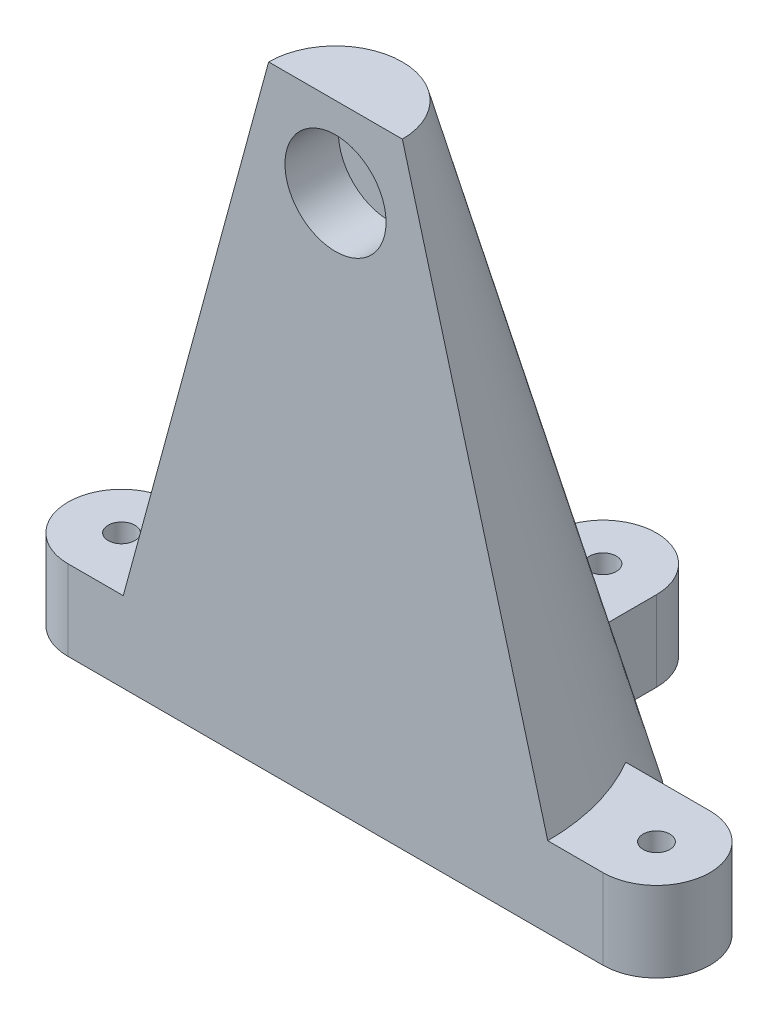
SolidWorks part; units mm, degrees
ref_plane "Front Plane" through (0, 0, 0) normal (0, 0, 1) x (1, 0, 0)
ref_plane "Top Plane" through (0, 0, 0) normal (0, 1, 0) x (1, 0, 0)
ref_plane "Right Plane" through (0, 0, 0) normal (1, 0, 0) x (0, 0, -1)
sketch "Sketch1" plane through (0, 0, 0) normal (0, 1, 0) x (1, 0, 0)
  line L0 (-22.225, 0) -> (22.225, 0)
  circle A0 centre (0, 0) radius 22.225 construction
  arc A1 (22.225, 0) -> (-22.225, 0) centre (0, 0) ccw
  point P6 (0, 0)
  point P7 (-22.2163, 0.6222)
  dimension "D1" = 44.45
ref_plane "Plane1" through (0, 58.42, 0) normal (0, 1, 0) x (1, 0, 0)
sketch "Sketch2" plane through (0, 58.42, 0) normal (0, 1, 0) x (1, 0, 0)
  line L0 (-22.225, 0) -> (22.225, 0) construction
  line L1 (-6.35, 0) -> (6.35, 0)
  circle A0 centre (0, 0) radius 6.35 construction
  arc A1 (6.35, 0) -> (-6.35, 0) centre (0, 0) ccw
  point P4 (-6.35, 0.1606)
  point P7 (0, 0)
  dimension "D1" = 12.7
loft "Loft1" add profiles "Sketch1", "Sketch2"
sketch "Sketch3" plane through (0, 0, 0) normal (0, 1, 0) x (1, 0, 0)
  line L0 (0, 0) -> (0, 25.4) construction
  line L1 (5.08, 25.4) -> (5.08, 10.16)
  line L2 (5.08, 10.16) -> (25.4, 10.16)
  line L3 (25.4, 0) -> (-25.4, 0)
  line L4 (-6.35, 0) -> (6.35, 0) construction
  line L5 (-5.08, 25.4) -> (-5.08, 10.16)
  line L6 (-5.08, 10.16) -> (-25.4, 10.16)
  arc A0 (-5.08, 25.4) -> (5.08, 25.4) centre (0, 25.4) cw
  arc A1 (25.4, 10.16) -> (25.4, 0) centre (25.4, 5.08) cw
  circle A2 centre (25.4, 5.08) radius 1.27
  circle A3 centre (-25.4, 5.08) radius 1.27
  arc A4 (-25.4, 10.16) -> (-25.4, 0) centre (-25.4, 5.08) ccw
  circle A5 centre (0, 25.4) radius 1.27
  point P19 (0, 0)
  point P20 (0, 30.8133)
  point P21 (0, 25.6327)
  dimension "D4" = 2.54
  dimension "D1" = 10.16
  dimension "D2" = 25.4
  dimension "D3" = 25.4
extrude "Boss-Extrude1" add sketch "Sketch3" along normal blind 7.62
sketch "Sketch4" plane through (0, 0, 0) normal (0, 0, 1) x (1, 0, 0)
  line L0 (0, 50.8) -> (0, 0) construction
  line L1 (-25.4, 0) -> (25.4, 0) construction
  circle A0 centre (0, 50.8) radius 4.8006
  dimension "D1" = 9.6012
  dimension "D2" = 50.8
extrude "Cut-Extrude1" cut sketch "Sketch4" against normal blind 5.08
